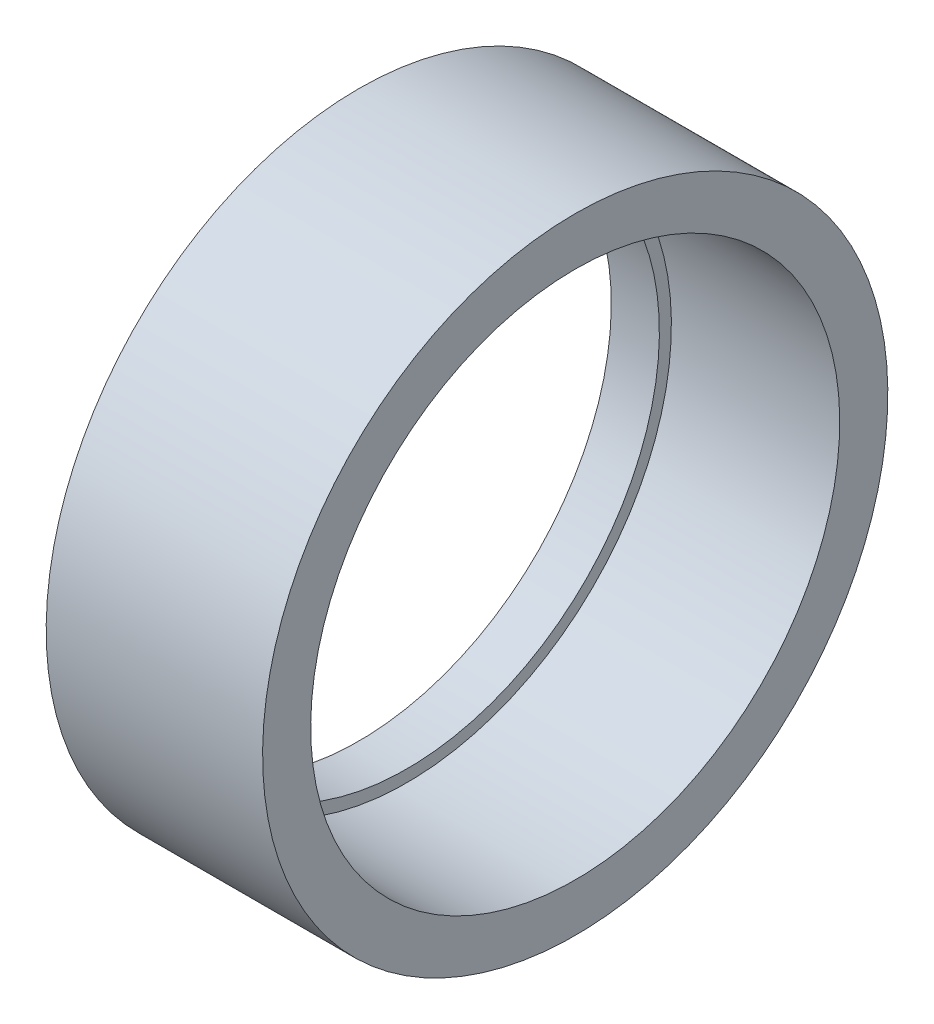
SolidWorks part; units mm, degrees
material "5052-H34"
ref_plane "Front Plane" through (0, 0, 0) normal (0, 0, 1) x (1, 0, 0)
ref_plane "Top Plane" through (0, 0, 0) normal (0, 1, 0) x (1, 0, 0)
ref_plane "Right Plane" through (0, 0, 0) normal (1, 0, 0) x (0, 0, -1)
sketch "Sketch2" plane through (0, 0, 0) normal (0, 0, 1) x (1, 0, 0)
  line L0 (0, 0) -> (0, 11) construction
  line L1 (0, 11) -> (0, 13)
  line L2 (0, 13) -> (-9, 13)
  line L3 (-9, 13) -> (-9, 10.5)
  line L4 (0, 11) -> (-7, 11)
  line L5 (-7, 11) -> (-7, 10.5)
  line L6 (0, 0) -> (-9, 0) construction
  line L7 (-9, 0) -> (-9, 10.5) construction
  line L8 (-7, 10.5) -> (-9, 10.5)
  dimension "D1" = 13
  dimension "D2" = 11
  dimension "D3" = 10.5
  dimension "D4" = 7
  dimension "D5" = 2
revolve "Revolve1" add sketch "Sketch2" angle 360 about L6
